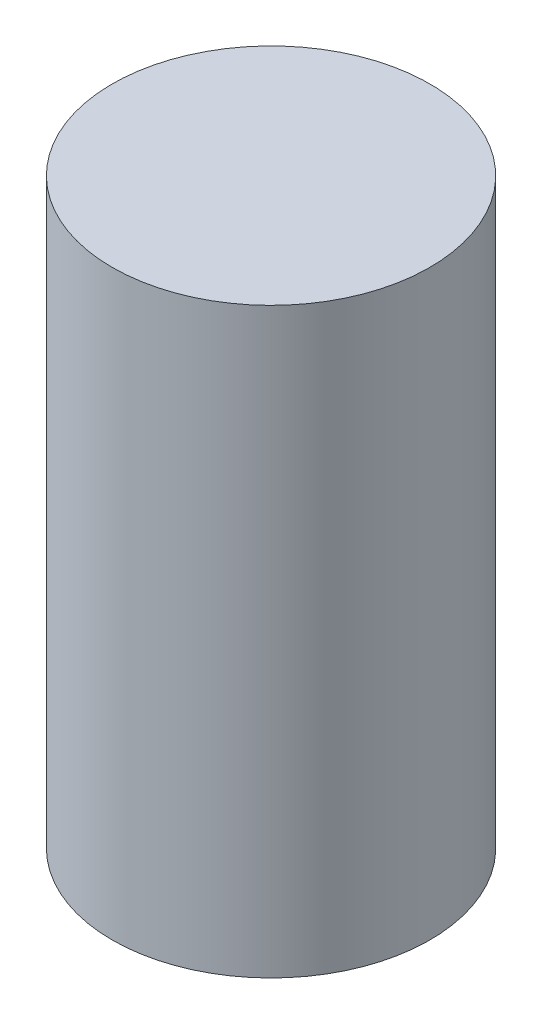
SolidWorks part; units mm, degrees
ref_plane "前视基准面" through (0, 0, 0) normal (0, 0, 1) x (1, 0, 0)
ref_plane "上视基准面" through (0, 0, 0) normal (0, 1, 0) x (1, 0, 0)
ref_plane "右视基准面" through (0, 0, 0) normal (1, 0, 0) x (0, 0, -1)
other "Configuration Table"
sketch "草图1" plane through (0, 0, 0) normal (0, 1, 0) x (1, 0, 0)
  line L5 (241.9495, -230.4137) -> (174.7692, -288.7901) construction
  line L6 (239.2741, -187.6955) -> (283.8763, -239.0243)
  line L10 (239.2741, -187.6955) -> (219.6484, -204.7493)
  line L11 (219.6484, -204.7493) -> (264.2506, -256.0781)
  line L12 (283.8763, -239.0243) -> (264.2506, -256.0781)
  line L13 (400, -400) -> (400, 400)
  line L14 (261.5752, -213.3599) -> (241.9495, -230.4137) construction
  line L15 (219.6484, -204.7493) -> (172.0938, -246.072) construction
  line L16 (152.4681, -263.1258) -> (197.0704, -314.4545)
  line L17 (197.0704, -314.4545) -> (216.6961, -297.4007)
  line L18 (216.6961, -297.4007) -> (172.0938, -246.072)
  line L19 (172.0938, -246.072) -> (152.4681, -263.1258)
  line L20 (162.281, -254.5989) -> (206.8832, -305.9276) construction
  line L21 (172.0938, -246.072) -> (264.2506, -256.0781) construction
  line L22 (218.1722, -251.075) -> (400, -400)
  line L24 (195.8711, -225.4106) -> (0, 0) construction
  line L25 (400, 0) -> (218.1722, -251.075)
  line L38 (0, -440) -> (0, 440) construction
  line L41 (-400, -400) -> (400, -400)
  line L42 (-400, 400) -> (400, 400)
  line L65 (-400, -400) -> (-400, 400)
  line L66 (274.0635, -247.5512) -> (229.4612, -196.2224) construction
  circle A0 centre (0, 0) radius 300
  circle A1 centre (0, 0) radius 150
  point P17 (174.7692, -288.7901)
  point P19 (218.1722, -251.075)
  point P20 (251.7624, -221.8868)
  point P21 (184.5821, -280.2632)
  point P22 (162.281, -254.5989)
  point P25 (229.4612, -196.2224)
  point P49 (-400, 0)
  dimension "D1" = 600
  dimension "D2" = 300
  dimension "D10" = 400
  dimension "D3" = 26
  dimension "D4" = 68
  dimension "D5" = 68
  dimension "D6" = 26
  dimension "D7" = 400
  dimension "D8" = 310
  dimension "D9" = 115
sketch "草图2" plane through (0, 0, 0) normal (0, 1, 0) x (1, 0, 0)
  circle A0 centre (0, 0) radius 300
  dimension "D1" = 600
extrude "凸台-拉伸1" add sketch "草图2" along normal blind 1000 and the other way blind 100
